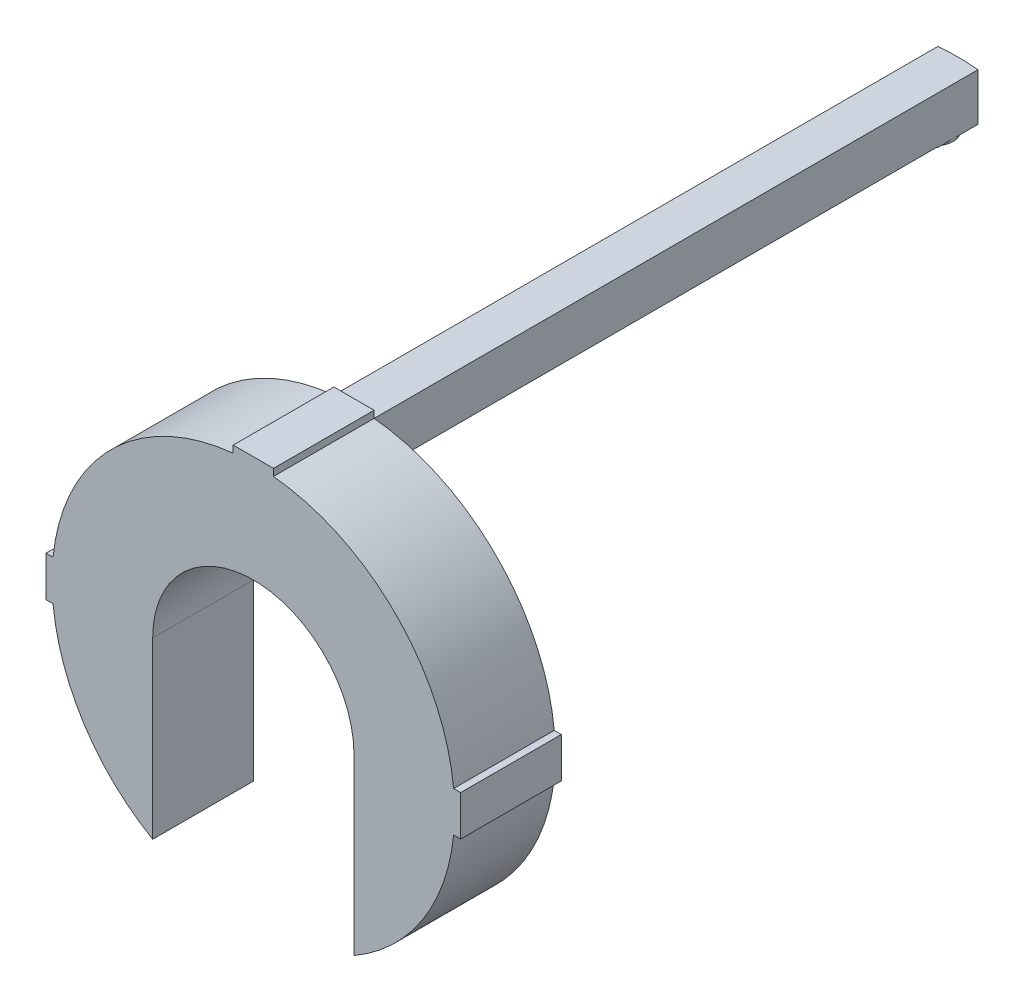
SolidWorks part; units mm, degrees
ref_plane "Ön Düzlem" through (0, 0, 0) normal (0, 0, 1) x (1, 0, 0)
ref_plane "Üst Düzlem" through (0, 0, 0) normal (0, 1, 0) x (1, 0, 0)
ref_plane "Sağ Düzlem" through (0, 0, 0) normal (1, 0, 0) x (0, 0, -1)
sketch "Sketch1" plane through (0, 0, 0) normal (0, 0, 1) x (1, 0, 0)
  circle A0 centre (0, 0) radius 5
  dimension "D1" = 10
extrude "Boss-Extrude1" add sketch "Sketch1" along normal blind 2.5
sketch "Sketch6" plane through (0, 0, 2.5) normal (0, 0, 1) x (1, 0, 0)
  line L1 (-5.15, 0.5) -> (-4.9, 0.5)
  line L2 (-5.15, 0.5) -> (-5.15, -0.5)
  line L3 (-5.15, -0.5) -> (-4.9, -0.5)
  line L4 (-4.9, 0.5) -> (-4.9, -0.5)
  point P4 (-4.9, 0)
  dimension "D1" = 0.25
  dimension "D2" = 1
  dimension "D3" = 4.9
extrude "Boss-Extrude4" add sketch "Sketch6" against normal blind 2.5
pattern_circular "CirPattern1" count 4 over 360 about axis through (0, 0, 0) along (0, 0, 1) of "Boss-Extrude4"
sketch "Sketch8" plane through (0, 0, 2.5) normal (0, 0, 1) x (1, 0, 0)
  circle A0 centre (0, 0) radius 2.5
  dimension "D1" = 5
extrude "Cut-Extrude3" cut sketch "Sketch8" against normal blind 1.25
sketch "Sketch9" plane through (0, 0, 0) normal (0, 0, -1) x (-1, 0, 0)
  line L0 (-0.5, 5.15) -> (0.5, 5.15) construction
  line L1 (-0.5, 5.15) -> (0.5, 5.15)
  line L2 (-0.5, 5.15) -> (-0.5, 3.8)
  line L3 (-0.5, 3.8) -> (0.5, 3.8)
  line L4 (0.5, 5.15) -> (0.5, 3.8)
  line L5 (0.5, 5.15) -> (0.5, 4.9749) construction
  line L6 (-0.5, 4.9749) -> (-0.5, 5.15) construction
  dimension "D1" = 3.8
extrude "Boss-Extrude5" add sketch "Sketch9" along normal blind 15
sketch "Sketch11" plane through (0, 0, 0) normal (0, 0, -1) x (-1, 0, 0)
  circle A0 centre (0, 0) radius 3.85
  dimension "D1" = 7.7
extrude "Cut-Extrude4" cut sketch "Sketch11" along normal blind 14
sketch "Sketch12" plane through (0, 5.15, 0) normal (0, 1, 0) x (1, 0, 0)
  line L0 (-0.5, 15) -> (0.5, 15) construction
  circle A0 centre (0, 14.4) radius 0.48
  dimension "D1" = 0.96
  dimension "D2" = 0.6
extrude "Boss-Extrude6" add sketch "Sketch12" against normal blind 7
sketch "Sketch13" plane through (0, 0, -15) normal (0, 0, -1) x (-1, 0, 0)
  circle A0 centre (0, 0) radius 3.75
  dimension "D1" = 7.5
extrude "Cut-Extrude5" cut sketch "Sketch13" against normal blind 7
sketch "Sketch14" plane through (0, 0, 0) normal (0, 0, -1) x (-1, 0, 0)
  circle A0 centre (0, 0) radius 5
  circle A1 centre (0, 0) radius 6.795
extrude "Cut-Extrude6" cut sketch "Sketch14" along normal blind 17
sketch "Sketch15" plane through (0, 0, 2.5) normal (0, 0, 1) x (1, 0, 0)
  line L0 (0, 0) -> (0, -5) construction
  line L1 (2.5, 0) -> (2.5, -5)
  line L2 (-2.5, 0) -> (-2.5, -5)
  arc A0 (2.5, 0) -> (-2.5, 0) centre (0, 0) ccw
  arc A1 (-2.5, -5) -> (2.5, -5) centre (0, -5) ccw
  point P3 (0, -2.5)
  dimension "D1" = 2.5
  dimension "D2" = 5
extrude "Cut-Extrude7" cut sketch "Sketch15" against normal blind 10
